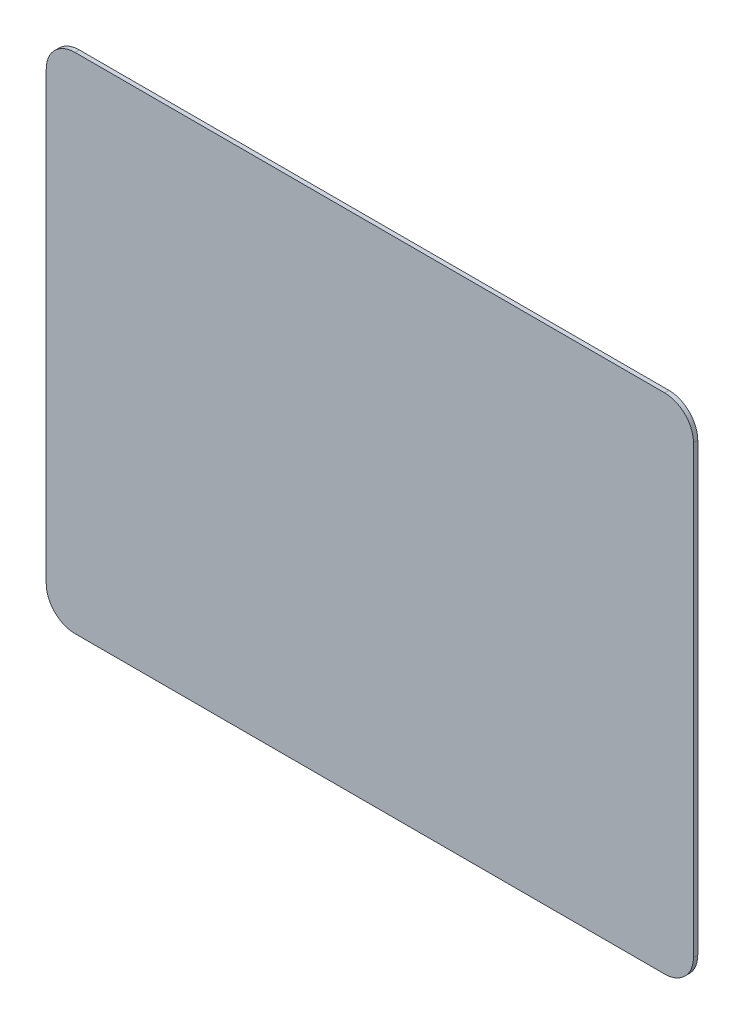
SolidWorks part; units mm, degrees
material "Q235A"
ref_plane "前视" through (0, 0, 0) normal (0, 0, 1) x (1, 0, 0)
ref_plane "上视" through (0, 0, 0) normal (0, 1, 0) x (1, 0, 0)
ref_plane "右视" through (0, 0, 0) normal (1, 0, 0) x (0, 0, -1)
sketch "草图1" plane through (0, 0, 0) normal (0, 0, 1) x (1, 0, 0)
  line L1 (225, -175) -> (-225, -175)
  line L2 (225, -175) -> (225, 175)
  line L3 (225, 175) -> (-225, 175)
  line L4 (-225, -175) -> (-225, 175)
  line L5 (225, -175) -> (-225, 175) construction
  line L6 (225, 175) -> (-225, -175) construction
  point P0 (0, 0)
  dimension "D1" = 450
  dimension "D2" = 350
extrude "凸台-拉伸1" add sketch "草图1" along normal blind 3
fillet "圆角1" radius 20 4 edges at (-225, -175, 1.5) (225, -175, 1.5) (-225, 175, 1.5) (225, 175, 1.5)
